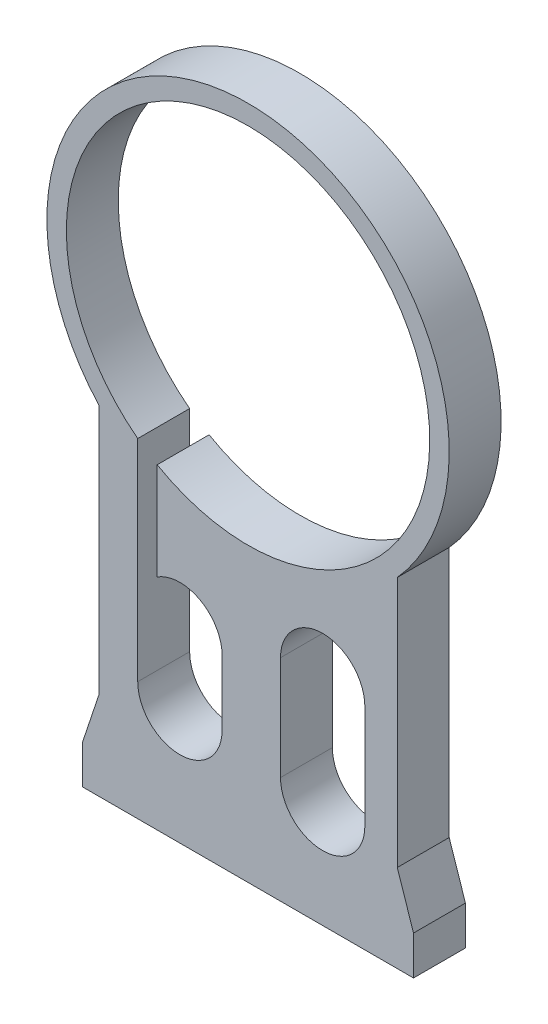
SolidWorks part; units mm, degrees
ref_plane "Płaszczyzna przednia" through (0, 0, 0) normal (0, 0, 1) x (1, 0, 0)
ref_plane "Płaszczyzna górna" through (0, 0, 0) normal (0, 1, 0) x (1, 0, 0)
ref_plane "Płaszczyzna prawa" through (0, 0, 0) normal (1, 0, 0) x (0, 0, -1)
sketch "Szkic1" plane through (0, 0, 0) normal (0, 0, 1) x (1, 0, 0)
  line L0 (0, 0) -> (0, 52) construction
  line L1 (12.75, 0) -> (-12.75, 0)
  line L2 (-12.75, 0) -> (-12.75, 3)
  line L3 (-12.75, 3) -> (-11.5, 6.75)
  line L4 (-11.5, 6.75) -> (-11.5, 26.1077)
  line L5 (-5.25, 14.15) -> (-5.25, 9.15) construction
  line L6 (-2, 14.15) -> (-2, 9.15)
  line L7 (-8.5, 14.15) -> (-8.5, 9.15)
  line L8 (5.75, 16.25) -> (5.75, 8.25) construction
  line L9 (9, 16.25) -> (9, 8.25)
  line L10 (2.5, 16.25) -> (2.5, 8.25)
  line L11 (-8.5, 14.15) -> (-8.5, 25.3757)
  line L12 (-7, 16.8886) -> (-7, 24.3756)
  line L13 (12.75, 0) -> (12.75, 3)
  line L14 (12.75, 3) -> (11.5, 6.75)
  line L15 (11.5, 6.75) -> (11.5, 26.1077)
  arc A1 (-7, 24.3756) -> (-8.5, 25.3757) centre (0, 36.5) ccw
  arc A2 (-2, 14.15) -> (-7, 16.8886) centre (-5.25, 14.15) ccw
  arc A3 (-8.5, 9.15) -> (-2, 9.15) centre (-5.25, 9.15) ccw
  arc A4 (9, 16.25) -> (2.5, 16.25) centre (5.75, 16.25) ccw
  arc A5 (2.5, 8.25) -> (9, 8.25) centre (5.75, 8.25) ccw
  arc A6 (11.5, 26.1077) -> (-11.5, 26.1077) centre (0, 36.5) ccw
  point P12 (-5.25, 11.65)
  point P19 (5.75, 12.25)
  point P28 (-12.75, 1.5)
  point P30 (-5.25, 5.9)
  point P35 (5.75, 19.5)
  point P36 (5.75, 5)
  dimension "D2" = 15.5
  dimension "D3" = 28
  dimension "D16" = 5
  dimension "D1" = 52
  dimension "D4" = 1.5
  dimension "D5" = 3
  dimension "D6" = 3.75
  dimension "D7" = 12.75
  dimension "D8" = 11.5
  dimension "D9" = 3
  dimension "D10" = 6.5
  dimension "D11" = 11.65
  dimension "D12" = 5.9
  dimension "D13" = 6.5
  dimension "D14" = 2.5
  dimension "D15" = 14.5
extrude "Dodanie-wyciągnięcie1" add sketch "Szkic1" along normal blind 4
